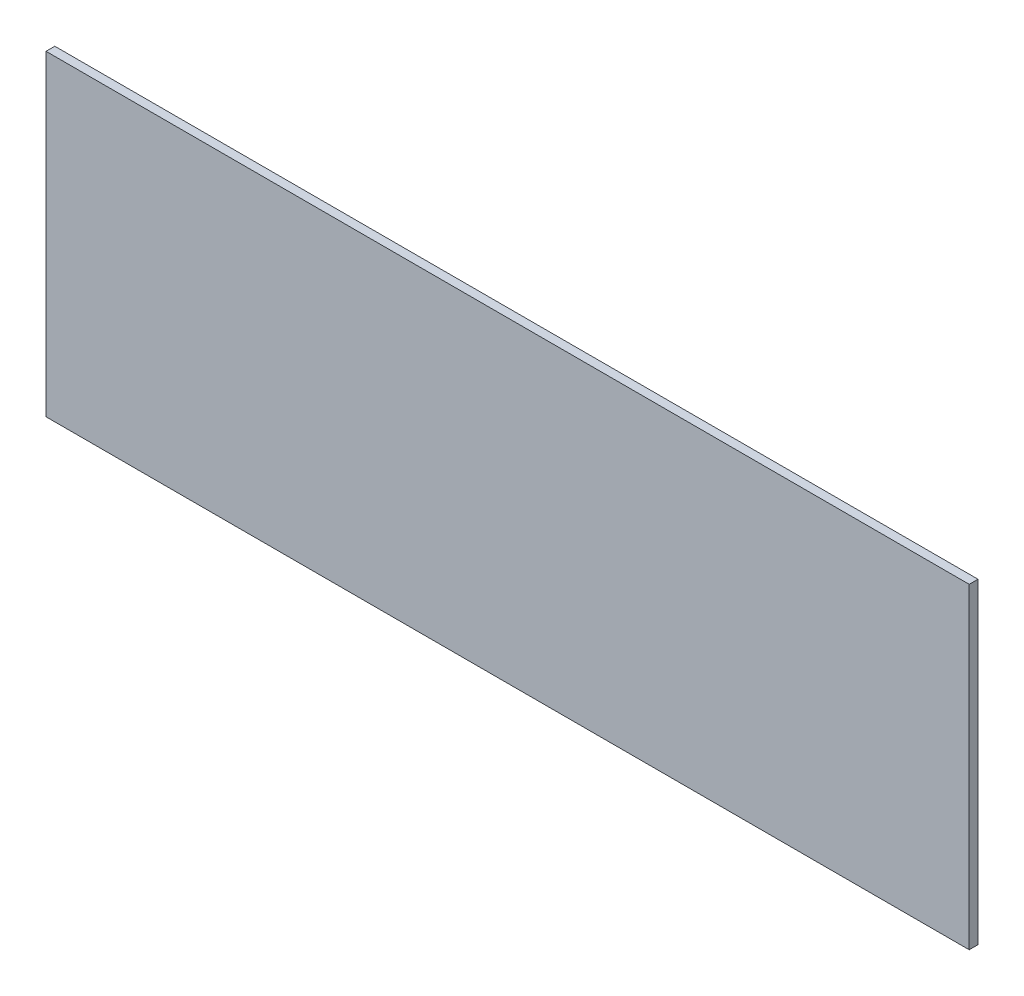
SolidWorks part; units mm, degrees
ref_plane "Front Plane" through (0, 0, 0) normal (0, 0, 1) x (1, 0, 0)
ref_plane "Top Plane" through (0, 0, 0) normal (0, 1, 0) x (1, 0, 0)
ref_plane "Right Plane" through (0, 0, 0) normal (1, 0, 0) x (0, 0, -1)
sketch "Sketch1" plane through (0, 0, 0) normal (0, 0, 1) x (1, 0, 0)
  line L1 (-105, -36) -> (105, -36)
  line L2 (-105, -36) -> (-105, 36)
  line L3 (-105, 36) -> (105, 36)
  line L4 (105, -36) -> (105, 36)
  line L5 (-105, -36) -> (105, 36) construction
  line L6 (-105, 36) -> (105, -36) construction
  point P0 (0, 0)
  dimension "D1" = 210
  dimension "D2" = 72
extrude "Boss-Extrude1" add sketch "Sketch1" along normal blind 2
